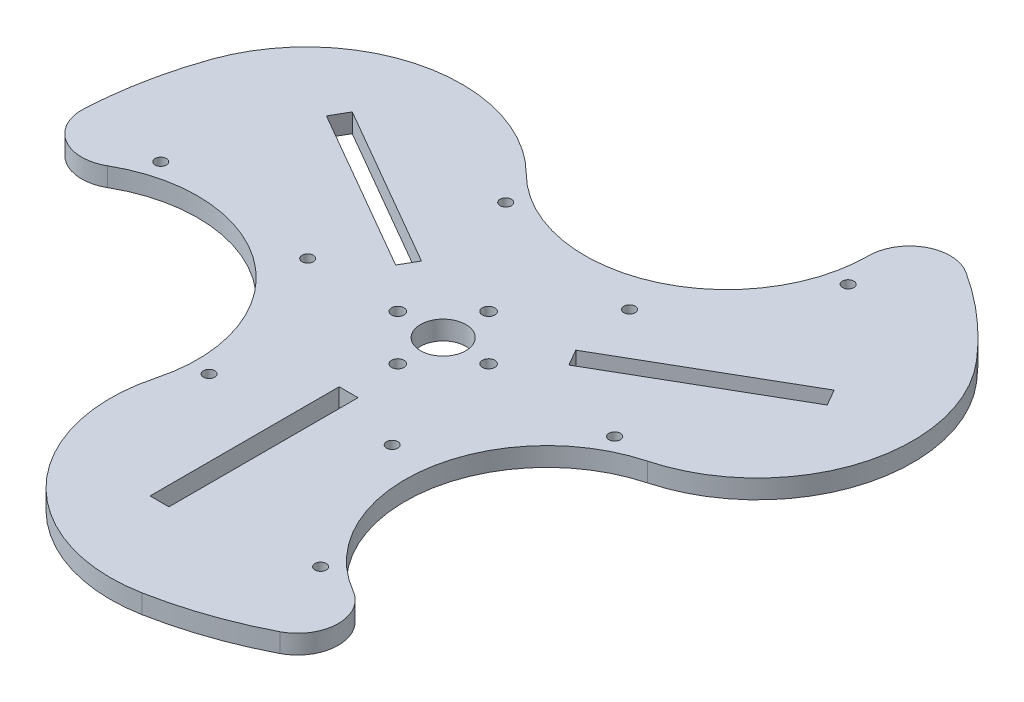
SolidWorks part; units mm, degrees
ref_plane "前基準面" through (0, 0, 0) normal (0, 0, 1) x (1, 0, 0)
ref_plane "上基準面" through (0, 0, 0) normal (0, 1, 0) x (1, 0, 0)
ref_plane "右基準面" through (0, 0, 0) normal (1, 0, 0) x (0, 0, -1)
sketch "草圖1" plane through (0, 0, 0) normal (0, 1, 0) x (1, 0, 0)
  line L2 (0, 75) -> (0, 0) construction
  line L3 (-64.9519, -37.5) -> (0, 0) construction
  line L4 (-28.5, 28.5) -> (28.5, 28.5) construction
  line L5 (-28.5, 28.5) -> (-28.5, -28.5) construction
  line L6 (-28.5, -28.5) -> (28.5, -28.5) construction
  line L7 (28.5, 28.5) -> (28.5, -28.5) construction
  line L8 (0, 0) -> (64.9519, -37.5) construction
  arc A20 (-54.1401, 84.0764) -> (-99.8824, 4.8485) centre (0, 0) ccw
  arc A21 (-37.5, 75) -> (37.5, 75) centre (0, 75) ccw
  circle A24 centre (0, 0) radius 6
  arc A25 (83.7019, -5.024) -> (46.2019, -69.976) centre (64.9519, -37.5) ccw
  arc A26 (-46.2019, -69.976) -> (-83.7019, -5.024) centre (-64.9519, -37.5) ccw
  arc A27 (99.8824, 4.8485) -> (54.1401, 84.0764) centre (0, 0) ccw
  arc A28 (-45.7423, -88.9249) -> (45.7423, -88.9249) centre (0, 0) ccw
  arc A29 (-54.1401, 84.0764) -> (-37.5, 75) centre (-48.2955, 75) cw
  arc A30 (54.1401, 84.0764) -> (37.5, 75) centre (48.2955, 75) ccw
  arc A31 (99.8824, 4.8485) -> (83.7019, -5.024) centre (89.0996, 4.3251) cw
  arc A32 (45.7423, -88.9249) -> (46.2019, -69.976) centre (40.8042, -79.3251) ccw
  arc A33 (-45.7423, -88.9249) -> (-46.2019, -69.976) centre (-40.8042, -79.3251) cw
  arc A34 (-99.8824, 4.8485) -> (-83.7019, -5.024) centre (-89.0996, 4.3251) ccw
  point P16 (0, 28.5)
  point P18 (-28.5, 0)
  dimension "D1" = 75
  dimension "D2" = 200
  dimension "D3" = 75
  dimension "D4" = 12
  dimension "D6" = 3
  dimension "D5" = 57
extrude "填料-伸長1" add sketch "草圖1" against normal blind 5
sketch "草圖5" plane through (0, 0, 0) normal (0, 1, 0) x (1, 0, 0)
  line L0 (0, 75) -> (-26.5165, 48.4835) construction
  line L1 (0, 75) -> (0, 0) construction
  line L2 (-63.7019, 39.6651) -> (-66.2019, 35.3349)
  line L3 (-63.7019, 39.6651) -> (-20.4006, 14.6651)
  line L4 (-66.2019, 35.3349) -> (-22.9006, 10.3349)
  line L5 (-20.4006, 14.6651) -> (-22.9006, 10.3349)
  line L6 (-21.6506, 12.5) -> (0, 0) construction
  line L7 (66.2019, 35.3349) -> (63.7019, 39.6651)
  line L8 (66.2019, 35.3349) -> (22.9006, 10.3349)
  line L9 (63.7019, 39.6651) -> (20.4006, 14.6651)
  line L10 (22.9006, 10.3349) -> (20.4006, 14.6651)
  line L11 (-2.5, -75) -> (2.5, -75)
  line L12 (-2.5, -75) -> (-2.5, -25)
  line L13 (2.5, -75) -> (2.5, -25)
  line L14 (-2.5, -25) -> (2.5, -25)
  arc A0 (-37.5, 75) -> (37.5, 75) centre (0, 75) ccw construction
  arc A1 (-37.5, 75) -> (37.5, 75) centre (0, 75) ccw construction
  arc A2 (-94.4114, 32.962) -> (-26.5165, 48.4835) centre (-55.5913, 19.4087) cw
  arc A3 (-54.1401, 84.0764) -> (-99.8824, 4.8485) centre (0, 0) ccw construction
  arc A4 (-37.5, 75) -> (-54.1401, 84.0764) centre (-48.2955, 75) ccw construction
  arc A5 (-37.5, 75) -> (-54.1401, 84.0764) centre (-48.2955, 75) ccw
  arc A6 (-54.1401, 84.0764) -> (-99.8824, 4.8485) centre (0, 0) ccw construction
  arc A7 (-94.4114, 32.962) -> (-54.1401, 84.0764) centre (0, 0) cw
  arc A8 (-37.5, 75) -> (-26.5165, 48.4835) centre (0, 75) ccw
  arc A9 (83.7019, -5.024) -> (99.8824, 4.8485) centre (89.0996, 4.3251) ccw
  arc A10 (83.7019, -5.024) -> (55.2462, -1.2778) centre (64.9519, -37.5) ccw
  arc A11 (75.7516, 65.2816) -> (55.2462, -1.2778) centre (44.6041, 38.4391) cw
  arc A12 (75.7516, 65.2816) -> (99.8824, 4.8485) centre (0, 0) cw
  arc A13 (-46.2019, -69.976) -> (-45.7423, -88.9249) centre (-40.8042, -79.3251) ccw
  arc A14 (-46.2019, -69.976) -> (-28.7297, -47.2057) centre (-64.9519, -37.5) ccw
  arc A15 (18.6598, -98.2436) -> (-28.7297, -47.2057) centre (10.9872, -57.8478) cw
  arc A16 (18.6598, -98.2436) -> (-45.7423, -88.9249) centre (0, 0) cw
  dimension "D2" = 3
  dimension "D1" = 45
  dimension "D3" = 60
  dimension "D4" = 50
  dimension "D5" = 5
  dimension "D6" = 25
extrude "除料-伸長1" cut sketch "草圖5" against normal through all both and the other way through all contours A16 A15 A14 A13 | A12 A11 A10 A9 | L5 L3 L2 L4 | L14 L12 L11 L13 | L10 L8 L7 L9 | A8 A5 A7 A2
sketch "草圖2" plane through (0, 0, 0) normal (0, 1, 0) x (1, 0, 0)
  line L0 (-12, 0) -> (12, 0)
  line L1 (0, -12) -> (0, 12)
  point P4 (0, 0)
  point P5 (0, 0)
  dimension "D1" = 24
sketch "草圖6" plane through (0, 0, 0) normal (0, 1, 0) x (1, 0, 0)
  line L0 (-83.7019, -5.024) -> (-64.9519, -37.5) construction
  line L1 (-64.9519, -37.5) -> (-28.7297, -47.2057) construction
  line L2 (-64.9519, -37.5) -> (-58.8473, -29.5443) construction
  line L3 (-77.5973, 2.9317) -> (-58.8473, -29.5443) construction
  line L4 (-58.8473, -29.5443) -> (-22.625, -39.25) construction
  line L5 (-58.8473, -29.5443) -> (-36.0187, 0.2065) construction
  line L6 (-77.5973, 2.9317) -> (-75.0973, -1.3985)
  arc A12 (-28.7297, -47.2057) -> (-83.7019, -5.024) centre (-64.9519, -37.5) ccw construction
  arc A13 (-28.7297, -47.2057) -> (-83.7019, -5.024) centre (-64.9519, -37.5) ccw construction
  circle A14 centre (-58.8473, -29.5443) radius 37.5 construction
  dimension "D1" = 67.5
  dimension "D2" = 5
hole_wizard "Ø3.0mm 定位孔1" positions "草圖7" profile "草圖8" hole size "Ø3.0" standard "ISO" end condition up to next
sketch "草圖7" plane through (0, 0, 0) normal (0, 1, 0) x (1, 0, 0)
  point P43 (-36.0187, 0.2065)
  point P46 (-22.625, -39.25)
  point P49 (-77.5973, 2.9317)
sketch "草圖8" plane through (-36.0187, 0, -0.2065) normal (1, 0, 0) x (0, 0, 1)
  line L0 (0, 0) -> (0, 5.001)
  line L1 (0, 5.001) -> (1.5, 5.001)
  line L2 (1.5, 5.001) -> (1.5, 0)
  line L5 (1.5, 0) -> (0, 0)
  line L11 (0, -6.35) -> (0, 107.95) construction
  dimension "貫穿孔直徑" = 3
  dimension "貫穿孔深度" = 5.001
pattern_circular "環狀複製排列1" count 3 every 120 about axis through (0, 0, 0) along (0, 1, 0) of "Ø3.0mm 定位孔1"
hole_wizard "M4 螺紋孔1" positions "草圖3" profile "草圖4" tap size "M4" standard "ISO" end condition through all
sketch "草圖3" plane through (0, 0, 0) normal (0, 1, 0) x (1, 0, 0)
  point P0 (0, 12)
  point P3 (12, 0)
  point P6 (0, -12)
  point P9 (-12, 0)
sketch "草圖4" plane through (0, 0, -12) normal (1, 0, 0) x (0, 0, 1)
  line L0 (0, 0) -> (0, 5)
  line L1 (0, 5) -> (1.65, 5)
  line L2 (1.65, 5) -> (1.65, 0)
  line L5 (1.65, 0) -> (0, 0)
  line L11 (0, -6.35) -> (0, 107.95) construction
  dimension "貫穿螺孔鑽直徑" = 3.3
  dimension "貫穿螺孔鑽深度" = 5
cosmetic thread "鑽孔螺紋1" parameters "D2"=4
cosmetic thread "鑽孔螺紋2" parameters "D2"=4
cosmetic thread "鑽孔螺紋3" parameters "D2"=4
cosmetic thread "鑽孔螺紋4" parameters "D2"=4
